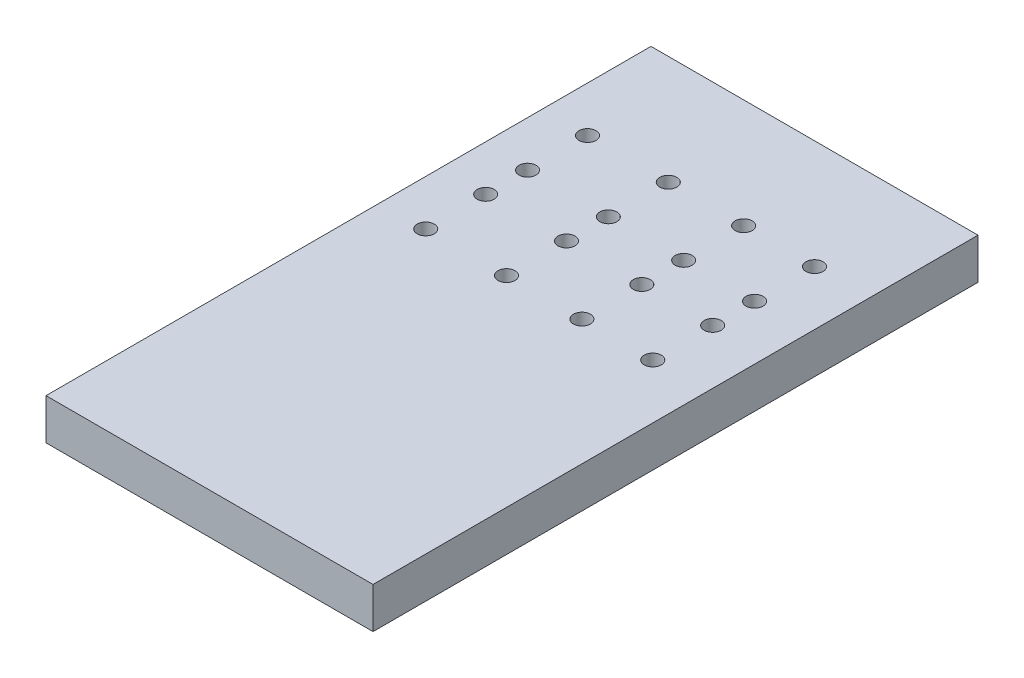
SolidWorks part; units mm, degrees
ref_plane "Front" through (0, 0, 0) normal (0, 0, 1) x (1, 0, 0)
ref_plane "Top" through (0, 0, 0) normal (0, 1, 0) x (1, 0, 0)
ref_plane "Right" through (0, 0, 0) normal (1, 0, 0) x (0, 0, -1)
sketch "Sketch1" plane through (0, 0, 0) normal (0, 1, 0) x (1, 0, 0)
  line L0 (-38.1, 45.085) -> (38.1, 45.085) construction
  line L1 (25.4, 19.3801) -> (25.4, -70.485) construction
  line L2 (-27.498, 23.3489) -> (-27.498, -70.485) construction
  line L3 (25.4, 33.0994) -> (25.4, 19.3801) construction
  line L4 (38.1, 21.3645) -> (38.1, 31.115) construction
  line L5 (38.1, 7.3945) -> (-38.1, 7.3945) construction
  line L6 (-8.6703, 23.3489) -> (-8.6703, -70.485) construction
  line L7 (-38.1, 31.115) -> (38.1, 31.115) construction
  line L8 (-38.1, 21.3645) -> (38.1, 21.3645) construction
  line L10 (-27.498, 70.485) -> (-27.498, 29.1306) construction
  line L11 (-8.6703, 70.485) -> (-8.6703, 29.1306) construction
  line L12 (8.89, 70.485) -> (8.89, -70.485) construction
  line L13 (25.4, 70.485) -> (25.4, 33.0994) construction
  line L15 (-38.1, -70.485) -> (38.1, -70.485)
  line L16 (-38.1, -70.485) -> (-38.1, 70.485)
  line L17 (-38.1, 70.485) -> (38.1, 70.485)
  line L18 (38.1, -70.485) -> (38.1, 70.485)
  line L19 (-38.1, -70.485) -> (38.1, 70.485) construction
  line L20 (-38.1, 70.485) -> (38.1, -70.485) construction
  circle A0 centre (-27.498, 45.085) radius 1.9844
  circle A1 centre (-27.498, 21.3645) radius 1.9844
  circle A2 centre (-27.498, 31.115) radius 1.9844
  circle A3 centre (-8.6703, 45.085) radius 1.9844
  circle A4 centre (8.89, 45.085) radius 1.9844
  circle A5 centre (25.4, 45.085) radius 1.9844
  circle A6 centre (25.4, 7.3945) radius 1.9844
  circle A7 centre (25.4, 31.115) radius 1.9844
  circle A8 centre (8.89, 31.115) radius 1.9844
  circle A9 centre (-8.6703, 21.3645) radius 1.9844
  circle A10 centre (8.89, 21.3645) radius 1.9844
  circle A11 centre (25.4, 21.3645) radius 1.9844
  circle A12 centre (8.89, 7.3945) radius 1.9844
  circle A13 centre (-8.6703, 7.3945) radius 1.9844
  circle A14 centre (-27.498, 7.3945) radius 1.9844
  circle A15 centre (-8.6703, 31.115) radius 1.9844
  point P53 (0, 0)
  point P55 (-38.1, 31.115)
  point P56 (-38.1, 21.3645)
  dimension "D5" = 3.9688
  dimension "D13" = 16.51
  dimension "D14" = 17.5603
  dimension "D32" = 140.97
  dimension "D33" = 76.2
  dimension "D4" = 12.7
  dimension "D2" = 18.8278
  dimension "D9" = 13.97
  dimension "D10" = 13.97
  dimension "D6" = 9.7505
  dimension "D7" = 25.4
extrude "Boss-Extrude1" add sketch "Sketch1" along normal blind 9.525
equation "\"D14@Sketch1\"=0.7508/2+0.6319/2"
equation "\"D10@Sketch1\"=\"D9@Sketch1\""
